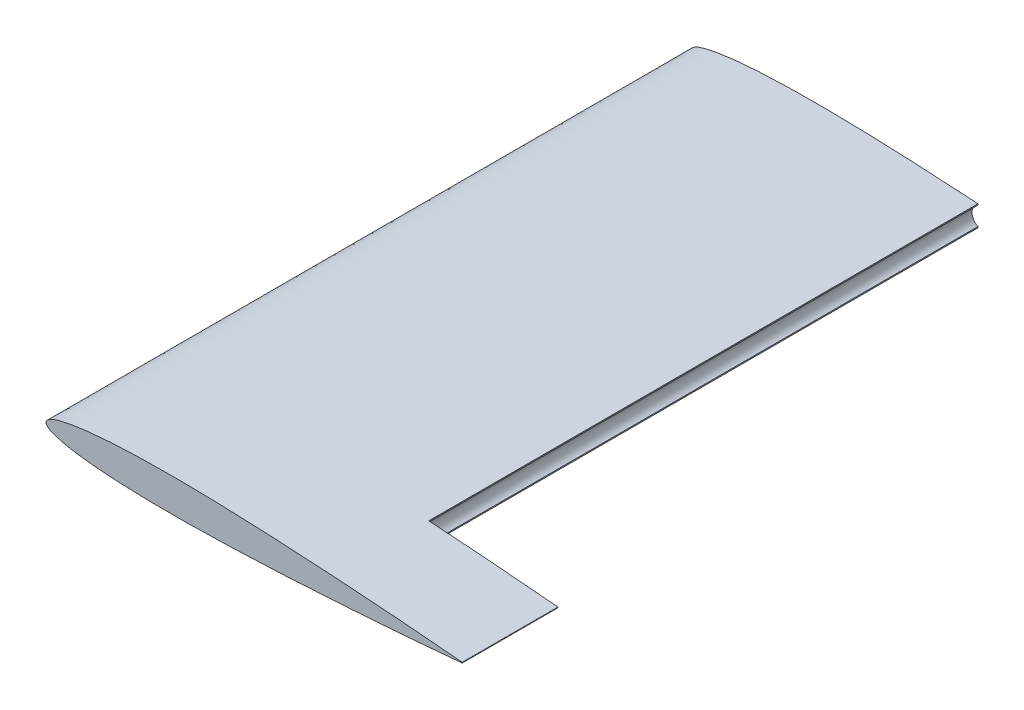
SolidWorks part; units mm, degrees
material "ABS generico"
ref_plane "Piano frontale" through (0, 0, 0) normal (0, 0, 1) x (1, 0, 0)
ref_plane "Piano superiore" through (0, 0, 0) normal (0, 1, 0) x (1, 0, 0)
ref_plane "Piano destro" through (0, 0, 0) normal (1, 0, 0) x (0, 0, -1)
curve "Curva1"
  spline degree 3 poles (100, 0.084, 0) (98.3335, 0.2367, 0) (95.0012, 0.5422, 0) (88.3356, 1.1109, 0) (80.0033, 1.7636, 0) (70.003, 2.4579, 0) (60.0031, 3.0617, 0) (50.003, 3.5521, 0) (40.0026, 3.9029, 0) (31.667, 4.0253, 0) (24.9992, 3.9769, 0) (19.9978, 3.845, 0) (14.9934, 3.5925, 0) (10.8272, 3.2377, 0) (7.4891, 2.814, 0) (4.9936, 2.4037, 0) (2.8496, 1.8679, 0) (1.1654, 1.321, 0) (-0.6646, 0, 0) (1.1654, -1.321, 0) (2.8496, -1.8679, 0) (4.9936, -2.4037, 0) (7.4891, -2.814, 0) (10.8272, -3.2377, 0) (14.9934, -3.5925, 0) (19.9978, -3.845, 0) (24.9992, -3.9769, 0) (31.667, -4.0253, 0) (40.0026, -3.9029, 0) (50.003, -3.5521, 0) (60.0031, -3.0617, 0) (70.003, -2.4579, 0) (80.0033, -1.7636, 0) (88.3356, -1.1109, 0) (95.0012, -0.5422, 0) (98.3335, -0.2367, 0) (100, -0.084, 0) knots 0 0 0 0 0.024876 0.049742 0.099443 0.149112 0.198751 0.248359 0.297937 0.347491 0.372267 0.397051 0.421859 0.446731 0.45922 0.471791 0.48456 0.491195 0.5 0.508805 0.51544 0.528209 0.54078 0.553269 0.578141 0.602949 0.627733 0.652509 0.702063 0.751641 0.801249 0.850888 0.900557 0.950258 0.975124 1 1 1 1
sketch "Schizzo1" plane through (0, 0, 0) normal (0, 0, 1) x (1, 0, 0)
  line L0 (70, 2.443) -> (70, -2.443) construction
  arc A1 (70, -2.443) -> (70, 2.443) centre (70, 0) cw
  spline S0 degree 3 poles (905.2539, 3897.2705) (397.5402, -70.8596) (246.6176, -12.3941) (88.3356, 1.1109) (80.0033, 1.7636) (70.003, 2.4579) (60.0031, 3.0617) (50.003, 3.5521) (40.0026, 3.9029) (31.667, 4.0253) (24.9992, 3.9769) (19.9978, 3.845) (14.9934, 3.5925) (10.8272, 3.2377) (7.4891, 2.814) (4.9936, 2.4037) (2.8496, 1.8679) (1.1654, 1.321) (-0.6646, 0) (1.1654, -1.321) (2.8496, -1.8679) (4.9936, -2.4037) (7.4891, -2.814) (10.8272, -3.2377) (14.9934, -3.5925) (19.9978, -3.845) (24.9992, -3.9769) (31.667, -4.0253) (40.0026, -3.9029) (50.003, -3.5521) (60.0031, -3.0617) (70.003, -2.4579) (80.0033, -1.7636) (88.3356, -1.1109) (246.6156, 12.3939) (397.5363, 70.8581) (905.2338, -3897.1134) knots -2.261938 -2.261938 -2.261938 -2.261938 0.024876 0.049742 0.099443 0.149112 0.198751 0.248359 0.297937 0.347491 0.372267 0.397051 0.421859 0.446731 0.45922 0.471791 0.48456 0.491195 0.5 0.508805 0.51544 0.528209 0.54078 0.553269 0.578141 0.602949 0.627733 0.652509 0.702063 0.751641 0.801249 0.850888 0.900557 0.950258 0.975124 3.261907 3.261907 3.261907 3.261907 only from (100, 0.084) to (100, -0.084) construction
  spline S1 degree 3 poles (70, 2.443) (66.6677, 2.6593) (60.0031, 3.0617) (50.003, 3.5521) (40.0026, 3.9029) (31.667, 4.0253) (24.9992, 3.9769) (19.9978, 3.845) (14.9934, 3.5925) (10.8272, 3.2377) (7.4891, 2.814) (4.9936, 2.4037) (2.8496, 1.8679) (1.1654, 1.321) (-0.6646, 0) (1.1654, -1.321) (2.8496, -1.8679) (4.9936, -2.4037) (7.4891, -2.814) (10.8272, -3.2377) (14.9934, -3.5925) (19.9978, -3.845) (24.9992, -3.9769) (31.667, -4.0253) (40.0026, -3.9029) (50.003, -3.5521) (60.0031, -3.0617) (66.6677, -2.6593) (70, -2.443) knots 0.149112 0.149112 0.149112 0.149112 0.198751 0.248359 0.297937 0.347491 0.372267 0.397051 0.421859 0.446731 0.45922 0.471791 0.48456 0.491195 0.5 0.508805 0.51544 0.528209 0.54078 0.553269 0.578141 0.602949 0.627733 0.652509 0.702063 0.751641 0.801249 0.850888 0.850888 0.850888 0.850888
  dimension "D1" = 4.886
extrude "CorpoFoam" add sketch "Schizzo1" along normal blind 132
sketch "Schizzo7" plane through (0, 0, 132) normal (0, 0, 1) x (1, 0, 0)
  arc A0 (100, 0.084) -> (100, -0.084) centre (100, 0) cw
  spline S0 degree 3 poles (774.5938, 2905.893) (370.1816, -60.6448) (232.5901, -11.1972) (88.3356, 1.1109) (80.0033, 1.7636) (70.003, 2.4579) (60.0031, 3.0617) (50.003, 3.5521) (40.0026, 3.9029) (31.667, 4.0253) (24.9992, 3.9769) (19.9978, 3.845) (14.9934, 3.5925) (10.8272, 3.2377) (7.4891, 2.814) (4.9936, 2.4037) (2.8496, 1.8679) (1.1654, 1.321) (-0.6646, 0) (1.1654, -1.321) (2.8496, -1.8679) (4.9936, -2.4037) (7.4891, -2.814) (10.8272, -3.2377) (14.9934, -3.5925) (19.9978, -3.845) (24.9992, -3.9769) (31.667, -4.0253) (40.0026, -3.9029) (50.003, -3.5521) (60.0031, -3.0617) (70.003, -2.4579) (80.0033, -1.7636) (88.3356, -1.1109) (232.5893, 11.1971) (370.1799, 60.6442) (774.5865, -2905.8392) knots -2.052665 -2.052665 -2.052665 -2.052665 0.024876 0.049742 0.099443 0.149112 0.198751 0.248359 0.297937 0.347491 0.372267 0.397051 0.421859 0.446731 0.45922 0.471791 0.48456 0.491195 0.5 0.508805 0.51544 0.528209 0.54078 0.553269 0.578141 0.602949 0.627733 0.652509 0.702063 0.751641 0.801249 0.850888 0.900557 0.950258 0.975124 3.052652 3.052652 3.052652 3.052652 only from (100, 0.084) to (100, -0.084) construction
  spline S1 degree 3 poles (100, 0.084) (98.3335, 0.2367) (95.0012, 0.5422) (88.3356, 1.1109) (80.0033, 1.7636) (70.003, 2.4579) (60.0031, 3.0617) (50.003, 3.5521) (40.0026, 3.9029) (31.667, 4.0253) (24.9992, 3.9769) (19.9978, 3.845) (14.9934, 3.5925) (10.8272, 3.2377) (7.4891, 2.814) (4.9936, 2.4037) (2.8496, 1.8679) (1.1654, 1.321) (-0.6646, 0) (1.1654, -1.321) (2.8496, -1.8679) (4.9936, -2.4037) (7.4891, -2.814) (10.8272, -3.2377) (14.9934, -3.5925) (19.9978, -3.845) (24.9992, -3.9769) (31.667, -4.0253) (40.0026, -3.9029) (50.003, -3.5521) (60.0031, -3.0617) (70.003, -2.4579) (80.0033, -1.7636) (88.3356, -1.1109) (95.0012, -0.5422) (98.3335, -0.2367) (100, -0.084) knots 0 0 0 0 0.024876 0.049742 0.099443 0.149112 0.198751 0.248359 0.297937 0.347491 0.372267 0.397051 0.421859 0.446731 0.45922 0.471791 0.48456 0.491195 0.5 0.508805 0.51544 0.528209 0.54078 0.553269 0.578141 0.602949 0.627733 0.652509 0.702063 0.751641 0.801249 0.850888 0.900557 0.950258 0.975124 1 1 1 1
extrude "FoamLaterale" add sketch "Schizzo7" along normal blind 23
sketch "Schizzo2" plane through (0, 0, 155) normal (0, 0, 1) x (1, 0, 0)
  line L0 (25, 0) -> (0, 0) construction
  circle A0 centre (25, 0) radius 3
  dimension "D1" = 6
  dimension "D2" = 25
extrude "ForoLongherone" cut sketch "Schizzo2" against normal through all
sketch "Schizzo6" plane through (0, 0, 0) normal (0, 0, -1) x (-1, 0, 0)
  line L0 (-72, 0) -> (-70, 0) construction
  line L1 (-72, 2.5074) -> (-69, 2.5074)
  line L2 (-72, 2.5074) -> (-72, -2.5074)
  line L3 (-72, -2.5074) -> (-69, -2.5074)
  line L4 (-69, 2.5074) -> (-69, -2.5074)
  spline S0 degree 3 poles (-70, 2.443) (-66.6677, 2.6593) (-60.0031, 3.0617) (-50.003, 3.5521) (-40.0026, 3.9029) (-31.667, 4.0253) (-24.9992, 3.9769) (-19.9978, 3.845) (-14.9934, 3.5925) (-10.8272, 3.2377) (-7.4891, 2.814) (-4.9936, 2.4037) (-2.8496, 1.8679) (-1.1654, 1.321) (0.6646, 0) (-1.1654, -1.321) (-2.8496, -1.8679) (-4.9936, -2.4037) (-7.4891, -2.814) (-10.8272, -3.2377) (-14.9934, -3.5925) (-19.9978, -3.845) (-24.9992, -3.9769) (-31.667, -4.0253) (-40.0026, -3.9029) (-50.003, -3.5521) (-60.0031, -3.0617) (-66.6677, -2.6593) (-70, -2.443) knots 0.149112 0.149112 0.149112 0.149112 0.198751 0.248359 0.297937 0.347491 0.372267 0.397051 0.421859 0.446731 0.45922 0.471791 0.48456 0.491195 0.5 0.508805 0.51544 0.528209 0.54078 0.553269 0.578141 0.602949 0.627733 0.652509 0.702063 0.751641 0.801249 0.850888 0.850888 0.850888 0.850888 construction
  dimension "D1" = 3
  dimension "D2" = 1
extrude "SmussoPosteriore" cut sketch "Schizzo6" against normal up to surface (132 mm away) up to face at (84.4102, -0.5898, 132)
sketch "Schizzo8" plane through (0, 0, 155) normal (0, 0, 1) x (1, 0, 0)
  line L0 (69, 1.5) -> (73, 1.5) construction
  line L9 (73, -1.5) -> (69, -1.5) construction
  arc A1 (100, -0.084) -> (100, 0.084) centre (100, 0) ccw construction
  arc A2 (69, 1.5) -> (69, -1.5) centre (71, 0) ccw construction
  arc A3 (73, -1.5) -> (73, 1.5) centre (71, 0) ccw construction
  circle A4 centre (71, 0) radius 1.5
  point P6 (100.084, 0)
  dimension "D1" = 3
  dimension "D3" = 5
  dimension "D2" = 29
  dimension "D4" = 4
extrude "ForoPerno" cut sketch "Schizzo8" against normal through all
sketch "Schizzo9" plane through (0, 0, 155) normal (0, 0, 1) x (1, 0, 0)
  circle A0 centre (25, 0) radius 3 construction
  circle A1 centre (25, 0) radius 3
  circle A2 centre (71, 0) radius 1.5 construction
  circle A3 centre (71, 0) radius 1.5
extrude "ChiusuraForiTerminali" add sketch "Schizzo9" against normal blind 5
sketch "Schizzo10" plane through (0, 0, 0) normal (0, 0, -1) x (-1, 0, 0)
  line L0 (-34.75, 0) -> (-25, 0) construction
  line L1 (-28, 3.995) -> (-28, -3.995) construction
  line L2 (-33, 3.9881) -> (-33, -3.9881) construction
  circle A0 centre (-34.75, 0) radius 1.75
  circle A1 centre (-25, 0) radius 3 construction
  spline S0 degree 3 poles (-69, 2.5074) (-66.0008, 2.6994) (-59.6695, 3.0781) (-50.003, 3.5521) (-40.0026, 3.9029) (-31.667, 4.0253) (-24.9992, 3.9769) (-19.9978, 3.845) (-14.9934, 3.5925) (-10.8272, 3.2377) (-7.4891, 2.814) (-4.9936, 2.4037) (-2.8496, 1.8679) (-1.1654, 1.321) (0.6646, 0) (-1.1654, -1.321) (-2.8496, -1.8679) (-4.9936, -2.4037) (-7.4891, -2.814) (-10.8272, -3.2377) (-14.9934, -3.5925) (-19.9978, -3.845) (-24.9992, -3.9769) (-31.667, -4.0253) (-40.0026, -3.9029) (-50.003, -3.5521) (-59.6695, -3.0781) (-66.0008, -2.6994) (-69, -2.5074) knots 0.154077 0.154077 0.154077 0.154077 0.198751 0.248359 0.297937 0.347491 0.372267 0.397051 0.421859 0.446731 0.45922 0.471791 0.48456 0.491195 0.5 0.508805 0.51544 0.528209 0.54078 0.553269 0.578141 0.602949 0.627733 0.652509 0.702063 0.751641 0.801249 0.845923 0.845923 0.845923 0.845923 construction
  dimension "D1" = 3.5
  dimension "D2" = 5
extrude "ForoVite" cut sketch "Schizzo10" against normal blind 13
ref_plane "PianoBullone" through (0, 0, 6) normal (0, 0, -1) x (-1, 0, 0)
sketch "Schizzo11" plane through (0, 0, 6) normal (0, 0, 1) x (1, 0, 0)
  line L0 (31.25, 0) -> (31.25, -7.2467)
  line L1 (31.25, 0) -> (33, -3.0311) construction
  line L2 (33, -3.0311) -> (36.5, -3.0311) construction
  line L3 (36.5, -3.0311) -> (38.25, 0) construction
  line L4 (38.25, 0) -> (36.5, 3.0311) construction
  line L5 (36.5, 3.0311) -> (33, 3.0311) construction
  line L6 (33, 3.0311) -> (31.25, 0) construction
  line L7 (31.25, -7.2467) -> (38.25, -7.2467)
  line L8 (38.25, -7.2467) -> (38.25, 0)
  line L9 (31.25, 0) -> (33, 3.0311)
  line L10 (33, 3.0311) -> (36.5, 3.0311)
  line L11 (36.5, 3.0311) -> (38.25, 0)
  circle A0 centre (34.75, 0) radius 3.0311 construction
  dimension "D1" = 3.5
  dimension "D2" = 7.2467
extrude "TaglioDado" cut sketch "Schizzo11" along normal blind 3
